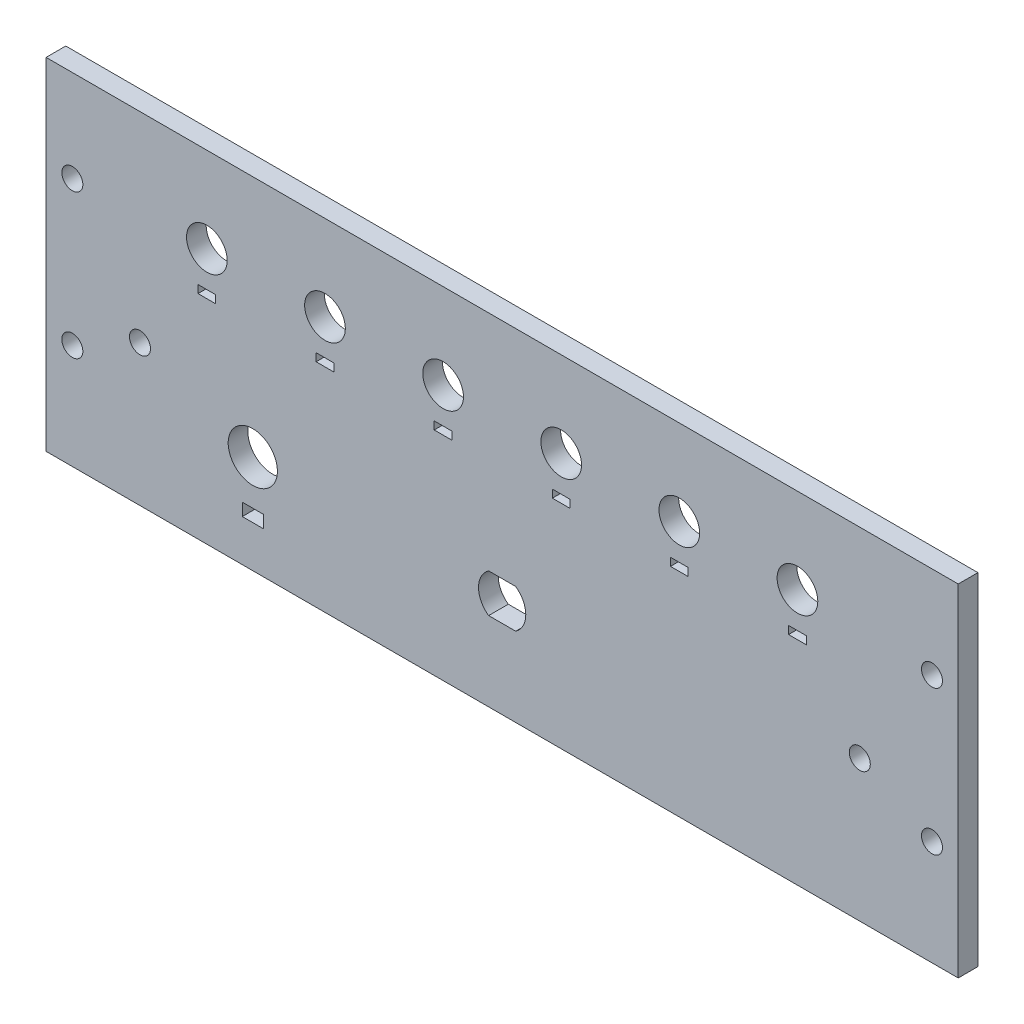
SolidWorks part; units mm, degrees
ref_plane "Front Plane" through (0, 0, 0) normal (0, 0, 1) x (1, 0, 0)
ref_plane "Top Plane" through (0, 0, 0) normal (0, 1, 0) x (1, 0, 0)
ref_plane "Right Plane" through (0, 0, 0) normal (1, 0, 0) x (0, 0, -1)
sketch "Sketch1" plane through (0, 0, 0) normal (0, 0, 1) x (1, 0, 0)
  line L0 (29.9, 6.35) -> (33.1, 6.35)
  line L1 (0, 0) -> (139, 0)
  line L2 (0, 0) -> (0, 52)
  line L3 (0, 52) -> (139, 52)
  line L4 (139, 0) -> (139, 52)
  line L5 (69.5, 52) -> (69.5, 0) construction
  line L17 (24.5, 39) -> (24.5, 33) construction
  line L20 (23.15, 32.4) -> (25.85, 32.4)
  line L27 (23.15, 32.4) -> (23.15, 33.6)
  line L28 (23.15, 33.6) -> (25.85, 33.6)
  line L29 (25.85, 32.4) -> (25.85, 33.6)
  line L30 (23.15, 32.4) -> (25.85, 33.6) construction
  line L31 (23.15, 33.6) -> (25.85, 32.4) construction
  line L34 (41.15, 32.4) -> (43.85, 32.4)
  line L35 (41.15, 32.4) -> (41.15, 33.6)
  line L36 (41.15, 33.6) -> (43.85, 33.6)
  line L37 (43.85, 32.4) -> (43.85, 33.6)
  line L38 (42.5, 39) -> (42.5, 33) construction
  line L39 (41.15, 32.4) -> (43.85, 33.6) construction
  line L40 (41.15, 33.6) -> (43.85, 32.4) construction
  line L41 (59.15, 32.4) -> (61.85, 32.4)
  line L42 (59.15, 32.4) -> (59.15, 33.6)
  line L43 (59.15, 33.6) -> (61.85, 33.6)
  line L44 (61.85, 32.4) -> (61.85, 33.6)
  line L45 (60.5, 39) -> (60.5, 33) construction
  line L46 (59.15, 32.4) -> (61.85, 33.6) construction
  line L47 (59.15, 33.6) -> (61.85, 32.4) construction
  line L48 (77.15, 32.4) -> (79.85, 32.4)
  line L49 (77.15, 32.4) -> (77.15, 33.6)
  line L50 (77.15, 33.6) -> (79.85, 33.6)
  line L51 (79.85, 32.4) -> (79.85, 33.6)
  line L52 (78.5, 39) -> (78.5, 33) construction
  line L53 (77.15, 32.4) -> (79.85, 33.6) construction
  line L54 (77.15, 33.6) -> (79.85, 32.4) construction
  line L55 (95.15, 32.4) -> (97.85, 32.4)
  line L56 (95.15, 32.4) -> (95.15, 33.6)
  line L57 (95.15, 33.6) -> (97.85, 33.6)
  line L58 (97.85, 32.4) -> (97.85, 33.6)
  line L59 (96.5, 39) -> (96.5, 33) construction
  line L60 (95.15, 32.4) -> (97.85, 33.6) construction
  line L61 (95.15, 33.6) -> (97.85, 32.4) construction
  line L62 (113.15, 32.4) -> (115.85, 32.4)
  line L63 (113.15, 32.4) -> (113.15, 33.6)
  line L64 (113.15, 33.6) -> (115.85, 33.6)
  line L65 (115.85, 32.4) -> (115.85, 33.6)
  line L66 (114.5, 39) -> (114.5, 33) construction
  line L67 (113.15, 32.4) -> (115.85, 33.6) construction
  line L68 (113.15, 33.6) -> (115.85, 32.4) construction
  line L69 (29.9, 6.35) -> (29.9, 8.25)
  line L70 (29.9, 8.25) -> (33.1, 8.25)
  line L71 (33.1, 6.35) -> (33.1, 8.25)
  line L72 (29.9, 6.35) -> (33.1, 8.25) construction
  line L73 (29.9, 8.25) -> (33.1, 6.35) construction
  line L74 (67.4366, 12.05) -> (71.5634, 12.05)
  line L75 (71.5634, 17.95) -> (67.4366, 17.95)
  circle A0 centre (24.5, 39) radius 3.1
  circle A4 centre (4, 38) radius 1.6
  circle A5 centre (135, 38) radius 1.6
  circle A6 centre (135, 16) radius 1.6
  circle A7 centre (4, 16) radius 1.6
  circle A9 centre (14.3091, 21.5) radius 1.6
  circle A11 centre (124, 21.5) radius 1.6
  circle A12 centre (42.5, 39) radius 3.1
  circle A13 centre (60.5, 39) radius 3.1
  circle A14 centre (78.5, 39) radius 3.1
  circle A15 centre (96.5, 39) radius 3.1
  circle A16 centre (114.5, 39) radius 3.1
  circle A17 centre (31.5, 15) radius 3.75
  arc A19 (67.4366, 17.95) -> (67.4366, 12.05) centre (69.5, 15) ccw
  arc A20 (71.5634, 12.05) -> (71.5634, 17.95) centre (69.5, 15) ccw
  circle A21 centre (69.5, 15) radius 3.6 construction
  point P8 (0, 26)
  point P14 (31.5, 7.3)
  point P36 (24.5, 33)
  dimension "D3" = 6.2
  dimension "D4" = 7.5
  dimension "D5" = 3.2
  dimension "D8" = 3.2
  dimension "D24" = 7.7
  dimension "D25" = 21.5
  dimension "D29" = 7.2
  dimension "D19" = 3.2
  dimension "D31" = 38
  dimension "D6" = 1.9
  dimension "D1" = 139
  dimension "D2" = 52
  dimension "D7" = 6
  dimension "D11" = 131
  dimension "D12" = 4
  dimension "D13" = 14
  dimension "D14" = 22
  dimension "D15" = 16
  dimension "D16" = 18
  dimension "D17" = 15
  dimension "D18" = 15
  dimension "D20" = 4
  dimension "D21" = 13
  dimension "D22" = 24.5
  dimension "D23" = 24.5
  dimension "D26" = 2.7
  dimension "D27" = 1.2
  dimension "D28" = 6
  dimension "D30" = 15
  dimension "D35" = 5.9
  dimension "D9" = 2
  dimension "D10" = 2
extrude "Boss-Extrude1" add sketch "Sketch1" along normal blind 3
